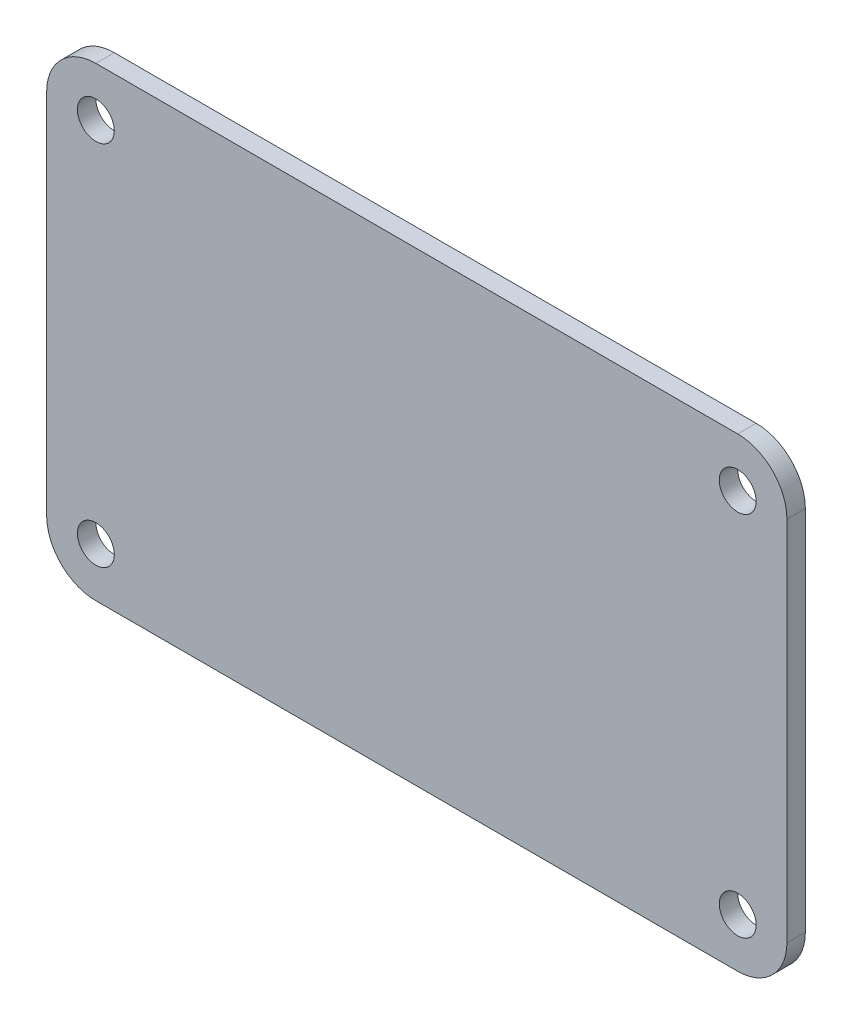
SolidWorks part; units mm, degrees
ref_plane "Front Plane" through (0, 0, 0) normal (0, 0, 1) x (1, 0, 0)
ref_plane "Top Plane" through (0, 0, 0) normal (0, 1, 0) x (1, 0, 0)
ref_plane "Right Plane" through (0, 0, 0) normal (1, 0, 0) x (0, 0, -1)
sketch "Sketch1" plane through (0, 0, 0) normal (0, 0, 1) x (1, 0, 0)
  line L1 (-26.095, 18.92) -> (26.095, 18.92)
  line L2 (-30.095, 14.92) -> (-30.095, -14.92)
  line L3 (-26.095, -18.92) -> (26.095, -18.92)
  line L4 (30.095, 14.92) -> (30.095, -14.92)
  line L5 (-30.095, 18.92) -> (30.095, -18.92) construction
  line L6 (-30.095, -18.92) -> (30.095, 18.92) construction
  circle A0 centre (-26.095, 14.92) radius 1.5
  circle A1 centre (-26.095, -14.92) radius 1.5
  circle A2 centre (26.095, 14.92) radius 1.5
  circle A3 centre (26.095, -14.92) radius 1.5
  arc A4 (26.095, -18.92) -> (30.095, -14.92) centre (26.095, -14.92) ccw
  arc A5 (26.095, 18.92) -> (30.095, 14.92) centre (26.095, 14.92) cw
  arc A6 (-30.095, -14.92) -> (-26.095, -18.92) centre (-26.095, -14.92) ccw
  arc A7 (-26.095, 18.92) -> (-30.095, 14.92) centre (-26.095, 14.92) ccw
  point P0 (0, 0)
  point P14 (0, 0)
  point P15 (0, 0)
  point P16 (0, 0)
  point P17 (0, 0)
  dimension "D3" = 3
  dimension "D8" = 4
  dimension "D1" = 60.19
  dimension "D2" = 37.84
  dimension "D4" = 4
  dimension "D5" = 4
  dimension "D6" = 4
  dimension "D7" = 4
extrude "Boss-Extrude1" add sketch "Sketch1" along normal blind 1.5
